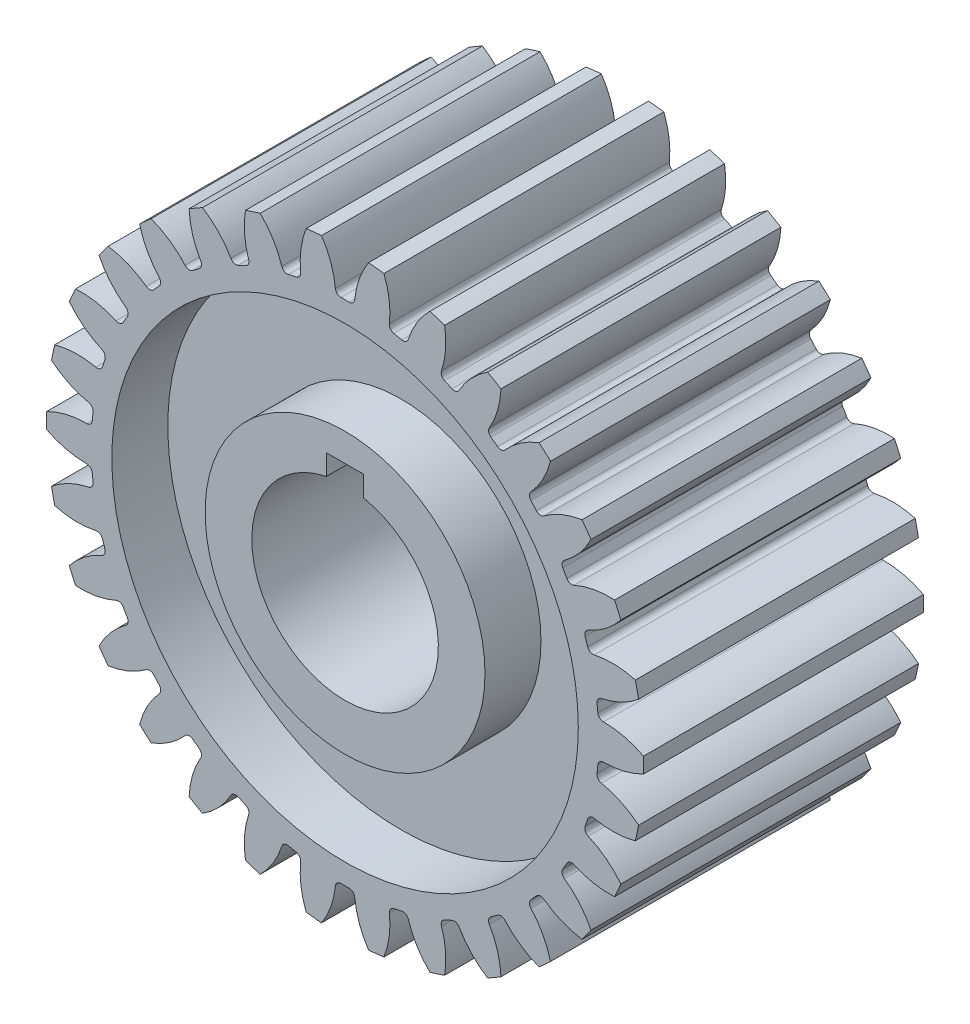
SolidWorks part; units mm, degrees
ref_plane "Front Plane" through (0, 0, 0) normal (0, 0, 1) x (1, 0, 0)
ref_plane "Top Plane" through (0, 0, 0) normal (0, 1, 0) x (1, 0, 0)
ref_plane "Right Plane" through (0, 0, 0) normal (1, 0, 0) x (0, 0, -1)
sketch "Sketch1" plane through (0, 0, 0) normal (0, 0, 1) x (1, 0, 0)
  circle A0 centre (0, 0) radius 16
  dimension "D1" = 32
extrude "Boss-Extrude1" add sketch "Sketch1" along normal mid plane 15
sketch "Sketch2" plane through (0, 0, 7.5) normal (0, 0, 1) x (1, 0, 0)
  line L1 (-1, 6) -> (1, 6)
  line L2 (-1, 6) -> (-1, 4.899)
  line L4 (1, 6) -> (1, 4.899)
  arc A0 (-1, 4.899) -> (1, 4.899) centre (0, 0) ccw
  point P3 (0, 5)
  dimension "D1" = 10
  dimension "D2" = 1
  dimension "D3" = 2
  dimension "D4" = 6
extrude "Cut-Extrude1" cut sketch "Sketch2" against normal through all
sketch "Sketch3" plane through (0, 0, 7.5) normal (0, 0, 1) x (1, 0, 0)
  circle A0 centre (0, 0) radius 12.5
  circle A1 centre (0, 0) radius 7.5
  dimension "D1" = 15
  dimension "D2" = 25
extrude "Cut-Extrude2" cut sketch "Sketch3" against normal blind 3
mirror "Mirror1" about plane through (0, 0, 0) normal (0, 0, 1) of "Cut-Extrude2"
sketch "Sketch4" plane through (0, 0, 7.5) normal (0, 0, 1) x (1, 0, 0)
  line L0 (0, 0) -> (0, 19.9711) construction
  line L1 (-0.2199, 13.6) -> (0.2199, 13.6)
  arc A0 (0.5184, 13.8707) -> (2.08, 16.88) centre (5.0567, 13.4256) cw
  arc A1 (-0.5184, 13.8707) -> (-2.08, 16.88) centre (-5.0567, 13.4256) ccw
  arc A2 (-2.08, 16.88) -> (2.08, 16.88) centre (0, -0.9994) cw
  arc A3 (0.2199, 13.6) -> (0.5184, 13.8707) centre (0.2199, 13.9) ccw
  arc A4 (-0.2199, 13.6) -> (-0.5184, 13.8707) centre (-0.2199, 13.9) cw
  point P11 (0, 13.6)
  point P13 (0.5, 13.6)
  point P16 (-0.5, 13.6)
  dimension "D3" = 1.58
  dimension "D5" = 4.56
  dimension "D6" = 18
  dimension "D7" = 0.3
  dimension "D1" = 0.5
  dimension "D2" = 13.6
  dimension "D4" = 3.28
extrude "Cut-Extrude3" cut sketch "Sketch4" against normal through all
pattern_circular "CirPattern1" count 30 over 360 about axis through (0, 0, 0) along (0, 0, 1) of "Cut-Extrude3"
